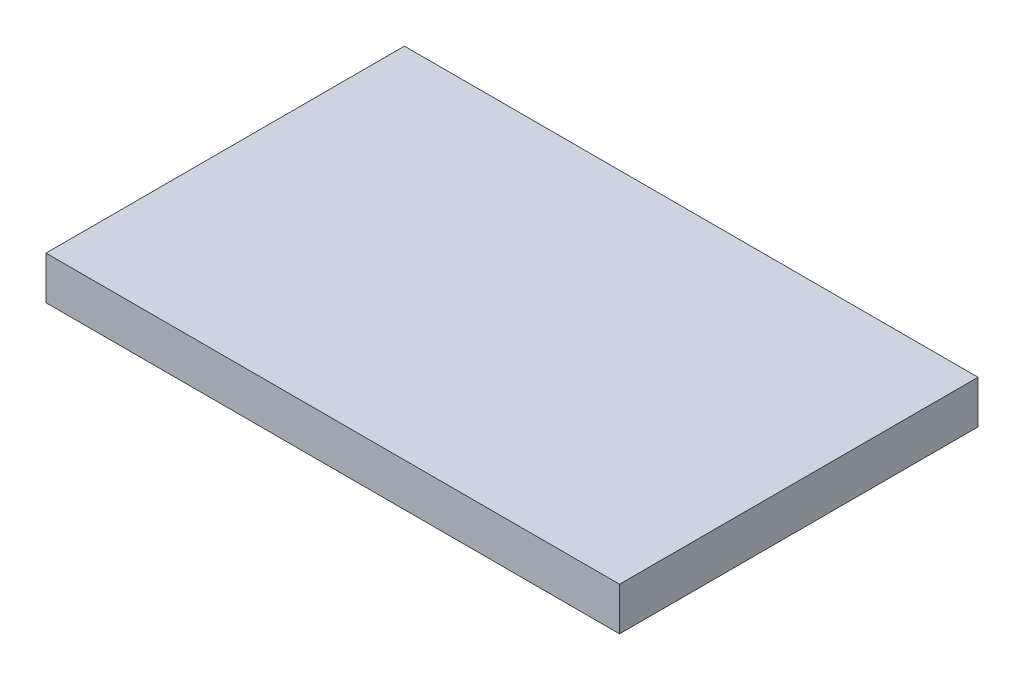
SolidWorks part; units mm, degrees
ref_plane "Front Plane" through (0, 0, 0) normal (0, 0, 1) x (1, 0, 0)
ref_plane "Top Plane" through (0, 0, 0) normal (0, 1, 0) x (1, 0, 0)
ref_plane "Right Plane" through (0, 0, 0) normal (1, 0, 0) x (0, 0, -1)
sketch "Sketch2" plane through (0, 0, 0) normal (0, 1, 0) x (1, 0, 0)
  line L1 (20, -12.5) -> (-20, -12.5)
  line L2 (20, -12.5) -> (20, 12.5)
  line L3 (20, 12.5) -> (-20, 12.5)
  line L4 (-20, -12.5) -> (-20, 12.5)
  line L5 (20, -12.5) -> (-20, 12.5) construction
  line L6 (20, 12.5) -> (-20, -12.5) construction
  point P0 (0, 0)
  dimension "D1" = 40
  dimension "D2" = 25
extrude "Boss-Extrude1" add sketch "Sketch2" against normal blind 3
sketch "Sketch3" [suppressed] plane through (0, 0, 0) normal (0, 1, 0) x (1, 0, 0)
  line L0 (20, 12.5) -> (-20, 12.5) construction
  line L1 (-19, 12.5) -> (-11.5, 12.5)
  line L2 (-19, 12.5) -> (-19, 2)
  line L3 (-19, 2) -> (-11.5, 2)
  line L4 (-11.5, 12.5) -> (-11.5, 2)
  line L5 (-20, 12.5) -> (-20, -12.5) construction
  dimension "D1" = 7.5
  dimension "D2" = 10.5
  dimension "D3" = 1
extrude "Boss-Extrude2" [suppressed] add sketch "Sketch3" along normal blind 10
sketch "Sketch4" [suppressed] plane through (0, 0, -2) normal (0, 0, 1) x (1, 0, 0)
  line L0 (-19, 7) -> (-18.1962, 10)
  line L1 (-19, 10) -> (-19, 0) construction
  line L2 (-19, 10) -> (-11.5, 10) construction
  line L3 (-18.1962, 10) -> (-19, 10)
  line L4 (-19, 10) -> (-19, 7)
  line L5 (-11.5, 7) -> (-13.2321, 10)
  line L6 (-11.5, 10) -> (-11.5, 0) construction
  line L7 (-13.2321, 10) -> (-11.5, 10)
  line L8 (-11.5, 10) -> (-11.5, 7)
  dimension "D1" = 3
  dimension "D2" = 3
  dimension "D3" = 15
  dimension "D4" = 30
extrude "Cut-Extrude1" [suppressed] cut sketch "Sketch4" against normal up to surface (10.5 mm away)
sketch "Sketch5" [suppressed] plane through (0, 10, 0) normal (0, 1, 0) x (1, 0, 0)
  line L0 (-13.2321, 12.5) -> (-18.1962, 12.5) construction
  line L1 (-17.4641, 7.522) -> (-13.9641, 7.522)
  line L2 (-17.4641, 7.522) -> (-17.4641, 7.222)
  line L3 (-17.4641, 7.222) -> (-13.9641, 7.222)
  line L4 (-13.9641, 7.522) -> (-13.9641, 7.222)
  line L5 (-19, 2) -> (-11.5, 2) construction
  circle A0 centre (-15.7141, 10) radius 1.75
  circle A1 centre (-15.7141, 4.5) radius 1.75
  point P10 (-15.7141, 12.5)
  point P11 (-15.7141, 7.522)
  dimension "D3" = 3.5
  dimension "D4" = 3.5
  dimension "D1" = 0.3
  dimension "D2" = 3.5
  dimension "D5" = 2.5
  dimension "D6" = 2.5
extrude "Cut-Extrude2" [suppressed] cut sketch "Sketch5" against normal blind 5
sketch "Sketch6" [suppressed] plane through (-19, 0, 0) normal (-1, 0, 0) x (0, 0, 1)
  line L0 (-2, 7) -> (-2, 0) construction
  line L1 (-12, 5.5) -> (-7.5, 5.5)
  line L2 (-12, 5.5) -> (-12, 1)
  line L3 (-12, 1) -> (-7.5, 1)
  line L4 (-7.5, 5.5) -> (-7.5, 1)
  line L5 (-12, 5.5) -> (-7.5, 1) construction
  line L6 (-12, 1) -> (-7.5, 5.5) construction
  line L7 (-7, 5.5) -> (-2.5, 5.5)
  line L8 (-7, 5.5) -> (-7, 1)
  line L9 (-7, 1) -> (-2.5, 1)
  line L10 (-2.5, 5.5) -> (-2.5, 1)
  line L11 (-7, 5.5) -> (-2.5, 1) construction
  line L12 (-7, 1) -> (-2.5, 5.5) construction
  line L13 (-12.5, 7) -> (-12.5, 0) construction
  line L14 (-12.5, 0) -> (-2, 0) construction
  point P0 (-9.75, 3.25)
  point P5 (-4.75, 3.25)
  dimension "D1" = 4.5
  dimension "D2" = 4.5
  dimension "D3" = 4.5
  dimension "D4" = 4.5
  dimension "D5" = 0.5
  dimension "D6" = 0.5
  dimension "D7" = 1
extrude "Cut-Extrude3" [suppressed] cut sketch "Sketch6" against normal blind 5
sketch "Sketch7" [suppressed] plane through (0, 0, 0) normal (0, 1, 0) x (1, 0, 0)
  line L0 (-20, 12.5) -> (-20, -12.5) construction
  line L1 (-11, -10) -> (-20, -10)
  line L2 (-11, -10) -> (-11, -2.5)
  line L3 (-11, -2.5) -> (-20, -2.5)
  line L4 (-20, -10) -> (-20, -2.5)
  line L5 (-11, -10) -> (-20, -2.5) construction
  line L6 (-11, -2.5) -> (-20, -10) construction
  line L7 (-20, -12.5) -> (20, -12.5) construction
  point P0 (-15.5, -6.25)
  dimension "D1" = 7.5
  dimension "D2" = 9
  dimension "D3" = 2.5
extrude "Boss-Extrude3" [suppressed] add sketch "Sketch7" along normal blind 3.5
sketch "Sketch8" [suppressed] plane through (-20, 0, 0) normal (-1, 0, 0) x (0, 0, 1)
  line L0 (6.25, 5.2143) -> (6.25, -0.441) construction
  line L1 (2.5, 3.5) -> (10, 3.5) construction
  line L2 (2.5, 3.5) -> (2.5, 0) construction
  line L3 (2.5, 0) -> (3.1127, 0)
  line L4 (2.5, 1.75) -> (2.5, 0)
  line L5 (10, 1.75) -> (10, 0)
  line L6 (10, 0) -> (9.3873, 0)
  spline S0 degree 3 poles (2.5, 1.75) (3.2855, 1.8357) (2.8866, -0.1418) (3.1127, 0) knots 0 0 0 0 1 1 1 1
  spline S1 degree 3 poles (10, 1.75) (9.2145, 1.8357) (9.6134, -0.1418) (9.3873, 0) knots 0 0 0 0 1 1 1 1
  point P4 (6.25, 3.5)
  line M15 (10, 0) -> (10, 3.5)
  line M17 (2.5, 3.5) -> (2.5, 0)
extrude "Cut-Extrude4" [suppressed] cut sketch "Sketch8" against normal blind 13.5 contours S0 L3 M17 | S1 L6 M15
fillet "Fillet1" [suppressed] radius 0.5
sketch "Sketch9" [suppressed] plane through (-20, 0, 0) normal (-1, 0, 0) x (0, 0, 1)
  line L0 (3.25, 0.25) -> (9.25, 0.25)
  line L1 (6.25, 3.8986) -> (6.25, 0.8013) construction
  line L2 (3, 3.5) -> (9.5, 3.5) construction
  line L3 (9.4263, 0) -> (12.5, 0) construction
  line L4 (9.4639, 3.25) -> (3.0361, 3.25)
  spline S0 degree 3 poles (9.25, 0.25) (9.2002, 0.8034) (9.2979, 1.1822) (9.4331, 1.8514) (9.7825, 1.9035) (9.8466, 2.3039) (9.7756, 2.7644) (9.8573, 3.2635) (9.4639, 3.25) knots 0 0 0 0 0.398944 0.460389 0.554943 0.650182 0.770421 1 1 1 1
  spline S1 degree 3 poles (3.25, 0.25) (3.2998, 0.8034) (3.2021, 1.1822) (3.0669, 1.8514) (2.7175, 1.9035) (2.6534, 2.3039) (2.7244, 2.7644) (2.6427, 3.2635) (3.0361, 3.25) knots 0 0 0 0 0.398944 0.460389 0.554943 0.650182 0.770421 1 1 1 1
  point P6 (6.25, 3.5)
  point P14 (6.25, 0.25)
  point P27 (6.25, 3.25)
  dimension "D1" = 3
  dimension "D2" = 0.25
  dimension "D3" = 0.25
extrude "Cut-Extrude5" [suppressed] cut sketch "Sketch9" against normal blind 8.5
sketch "Sketch10" [suppressed] plane through (0, 0, 0) normal (0, 1, 0) x (1, 0, 0)
  line L0 (-11.5, 2) -> (-11.5, 12.5) construction
  line L1 (-10, 9.5) -> (-7.5, 9.5)
  line L2 (-10, 9.5) -> (-10, 4.5)
  line L3 (-10, 4.5) -> (-7.5, 4.5)
  line L4 (-7.5, 9.5) -> (-7.5, 4.5)
  line L5 (-10, 9.5) -> (-7.5, 4.5) construction
  line L6 (-10, 4.5) -> (-7.5, 9.5) construction
  line L7 (20, 12.5) -> (-11.5, 12.5) construction
  point P0 (-8.75, 7)
  dimension "D1" = 5
  dimension "D2" = 2.5
  dimension "D3" = 1.5
  dimension "D4" = 3
extrude "Boss-Extrude4" [suppressed] add sketch "Sketch10" along normal blind 2
sketch "Sketch11" [suppressed] plane through (0, 2, 0) normal (0, 1, 0) x (1, 0, 0)
  line L0 (-7.5, 9.5) -> (-10, 9.5) construction
  line L1 (-8.5, 8) -> (-9, 8)
  line L2 (-8.5, 8) -> (-8.5, 8.5)
  line L3 (-8.5, 8.5) -> (-9, 8.5)
  line L4 (-9, 8) -> (-9, 8.5)
  line L5 (-8.5, 8) -> (-9, 8.5) construction
  line L6 (-8.5, 8.5) -> (-9, 8) construction
  line L7 (-8.5027, 5.5) -> (-9.0027, 5.5)
  line L8 (-8.5027, 5.5) -> (-8.5027, 6)
  line L9 (-8.5027, 6) -> (-9.0027, 6)
  line L10 (-9.0027, 5.5) -> (-9.0027, 6)
  line L11 (-8.5027, 5.5) -> (-9.0027, 6) construction
  line L12 (-8.5027, 6) -> (-9.0027, 5.5) construction
  line L13 (-7.5, 4.5) -> (-7.5, 9.5) construction
  line L14 (-10, 4.5) -> (-7.5, 4.5) construction
  point P0 (-8.75, 8.25)
  point P5 (-8.7527, 5.75)
  dimension "D1" = 0.5
  dimension "D2" = 0.5
  dimension "D3" = 0.5
  dimension "D4" = 0.5
  dimension "D5" = 1.25
  dimension "D6" = 1.25
  dimension "D7" = 1.2527
  dimension "D8" = 1.25
extrude "Boss-Extrude5" [suppressed] add sketch "Sketch11" along normal blind 5
sketch "Sketch12" [suppressed] plane through (0, 0, 0) normal (0, 1, 0) x (1, 0, 0)
  line L0 (-11, -9.5) -> (-11, -3) construction
  line L1 (-8.5, -9.75) -> (1.5, -9.75)
  line L2 (-8.5, -9.75) -> (-8.5, -12.25)
  line L3 (-8.5, -12.25) -> (1.5, -12.25)
  line L4 (1.5, -9.75) -> (1.5, -12.25)
  line L5 (-20, -12.5) -> (20, -12.5) construction
  dimension "D1" = 2.5
  dimension "D2" = 10
  dimension "D3" = 2.5
  dimension "D4" = 0.25
extrude "Boss-Extrude6" [suppressed] add sketch "Sketch12" along normal blind 2
sketch "Sketch13" [suppressed] plane through (0, 2, 0) normal (0, 1, 0) x (1, 0, 0)
  line L0 (-8.5, -9.75) -> (-8.5, -12.25) construction
  line L1 (-7, -11.25) -> (-7.5, -11.25)
  line L2 (-7, -11.25) -> (-7, -10.75)
  line L3 (-7, -10.75) -> (-7.5, -10.75)
  line L4 (-7.5, -11.25) -> (-7.5, -10.75)
  line L5 (-7, -11.25) -> (-7.5, -10.75) construction
  line L6 (-7, -10.75) -> (-7.5, -11.25) construction
  line L8 (1.5, -9.75) -> (-8.5, -9.75) construction
  line L9 (-5, -11.25) -> (-5, -10.75)
  line L10 (-4.5, -10.75) -> (-5, -10.75)
  line L11 (-4.5, -11.25) -> (-4.5, -10.75)
  line L12 (-4.5, -11.25) -> (-5, -11.25)
  line L13 (-2.5, -11.25) -> (-2.5, -10.75)
  line L14 (-2, -10.75) -> (-2.5, -10.75)
  line L15 (-2, -11.25) -> (-2, -10.75)
  line L16 (-2, -11.25) -> (-2.5, -11.25)
  line L17 (0, -11.25) -> (0, -10.75)
  line L18 (0.5, -10.75) -> (0, -10.75)
  line L19 (0.5, -11.25) -> (0.5, -10.75)
  line L20 (0.5, -11.25) -> (0, -11.25)
  point P0 (-7.25, -11)
  dimension "D1" = 1.25
  dimension "D2" = 1.25
  dimension "D3" = 0.5
  dimension "D4" = 0.5
  dimension "D5" = 4
extrude "Boss-Extrude7" [suppressed] add sketch "Sketch13" along normal blind 5
sketch "Sketch14" [suppressed] plane through (0, 0, 0) normal (0, 1, 0) x (1, 0, 0)
  line L0 (-7.5, 4.5) -> (-7.5, 9.5) construction
  line L1 (-6.5, 5.5) -> (1.5, 5.5)
  line L2 (-6.5, 5.5) -> (-6.5, 1.5)
  line L3 (-6.5, 1.5) -> (1.5, 1.5)
  line L4 (1.5, 5.5) -> (1.5, 1.5)
  line L5 (-8.5, -3.5) -> (1.5, -3.5)
  line L6 (-8.5, -3.5) -> (-8.5, -7.5)
  line L7 (-8.5, -7.5) -> (1.5, -7.5)
  line L8 (1.5, -3.5) -> (1.5, -7.5)
  line L9 (20, 12.5) -> (-11.5, 12.5) construction
  dimension "D1" = 8
  dimension "D2" = 4
  dimension "D3" = 4
  dimension "D4" = 10
  dimension "D5" = 1
  dimension "D6" = 7
  dimension "D7" = 5
extrude "Boss-Extrude8" [suppressed] add sketch "Sketch14" along normal blind 1
sketch "Sketch15" [suppressed] plane through (1.5, 0, 0) normal (1, 0, 0) x (0, 0, -1)
  line L0 (1.5, 0.7025) -> (1.3027, 0.7025)
  line L1 (1.5, 1) -> (1.5, 0) construction
  line L2 (1.0838, 0.6521) -> (0.9577, 0.5907)
  line L3 (0.704, 0.3042) -> (0.599, 0)
  line L4 (-12.5, 0) -> (12.5, 0) construction
  line L5 (0.599, 0) -> (0.8295, 0)
  line L6 (0.8295, 0) -> (0.9119, 0.2391)
  line L7 (1.1657, 0.5256) -> (1.216, 0.5501)
  line L8 (1.216, 0.5501) -> (1.5, 0.5501)
  line L9 (3.5, 2.4985) -> (3.5, 0.0788) construction
  line L10 (1.5, 1) -> (5.5, 1) construction
  line L11 (1.5, 0.7025) -> (1.5, 0.5501)
  line L12 (5.5, 0.7025) -> (5.5, 0.5501)
  line L13 (5.784, 0.5501) -> (5.5, 0.5501)
  line L14 (5.8343, 0.5256) -> (5.784, 0.5501)
  line L15 (6.1705, 0) -> (6.0881, 0.2391)
  line L16 (6.401, 0) -> (6.1705, 0)
  line L17 (6.296, 0.3042) -> (6.401, 0)
  line L18 (5.9162, 0.6521) -> (6.0423, 0.5907)
  line L19 (5.5, 0.7025) -> (5.6973, 0.7025)
  arc A0 (1.3027, 0.7025) -> (1.0838, 0.6521) centre (1.3027, 0.2025) ccw
  arc A1 (0.9119, 0.2391) -> (1.1657, 0.5256) centre (1.3846, 0.076) cw
  arc A2 (0.704, 0.3042) -> (0.9577, 0.5907) centre (1.1767, 0.1412) cw
  arc A3 (6.296, 0.3042) -> (6.0423, 0.5907) centre (5.8233, 0.1412) ccw
  arc A4 (6.0881, 0.2391) -> (5.8343, 0.5256) centre (5.6154, 0.076) ccw
  arc A5 (5.6973, 0.7025) -> (5.9162, 0.6521) centre (5.6973, 0.2025) cw
  point P16 (3.5, 1)
  dimension "D1" = 0.5
extrude "Boss-Extrude9" [suppressed] add sketch "Sketch15" against normal up to surface (8 mm away)
sketch "Sketch16" [suppressed] plane through (1.5, 0, 0) normal (1, 0, 0) x (0, 0, -1)
  line L0 (-7.5, 0.6782) -> (-7.7045, 0.6782)
  line L1 (-7.5, 1) -> (-7.5, 0) construction
  line L2 (-7.8691, 0.6503) -> (-7.9154, 0.6342)
  line L3 (-8.1339, 0.4833) -> (-8.2332, 0.3648)
  line L4 (-8.3282, 0.1901) -> (-8.3864, 0)
  line L5 (-12.5, 0) -> (12.5, 0) construction
  line L6 (-8.3864, 0) -> (-8.2252, 0)
  line L7 (-8.2252, 0) -> (-8.1768, 0.1579)
  line L8 (-8.0819, 0.3327) -> (-8.0568, 0.3626)
  line L9 (-7.9199, 0.4766) -> (-7.8668, 0.5066)
  line L10 (-7.6206, 0.5714) -> (-7.5, 0.5714)
  line L11 (-7.5, 0.6782) -> (-7.5, 0.5714)
  line L12 (-5.5, 2.2485) -> (-5.5, -1.2373) construction
  line L13 (-7.5, 1) -> (-3.5, 1) construction
  line L14 (-3.5, 0.6782) -> (-3.5, 0.5714)
  line L15 (-3.3794, 0.5714) -> (-3.5, 0.5714)
  line L16 (-3.0801, 0.4766) -> (-3.1332, 0.5066)
  line L17 (-2.9181, 0.3327) -> (-2.9432, 0.3626)
  line L18 (-2.7748, 0) -> (-2.8232, 0.1579)
  line L19 (-2.6136, 0) -> (-2.7748, 0)
  line L20 (-2.6718, 0.1901) -> (-2.6136, 0)
  line L21 (-2.8661, 0.4833) -> (-2.7668, 0.3648)
  line L22 (-3.1309, 0.6503) -> (-3.0846, 0.6342)
  line L23 (-3.5, 0.6782) -> (-3.2955, 0.6782)
  arc A1 (-7.7045, 0.6782) -> (-7.8691, 0.6503) centre (-7.7045, 0.1782) ccw
  arc A2 (-7.8668, 0.5066) -> (-7.6206, 0.5714) centre (-7.6206, 0.0714) cw
  arc A3 (-8.0568, 0.3626) -> (-7.9199, 0.4766) centre (-7.6737, 0.0414) cw
  arc A4 (-8.1768, 0.1579) -> (-8.0819, 0.3327) centre (-7.6987, 0.0115) cw
  arc A5 (-8.2332, 0.3648) -> (-8.3282, 0.1901) centre (-7.8501, 0.0436) ccw
  arc A6 (-7.9154, 0.6342) -> (-8.1339, 0.4833) centre (-7.7508, 0.1621) ccw
  arc A7 (-3.0846, 0.6342) -> (-2.8661, 0.4833) centre (-3.2492, 0.1621) cw
  arc A8 (-2.7668, 0.3648) -> (-2.6718, 0.1901) centre (-3.1499, 0.0436) cw
  arc A9 (-2.8232, 0.1579) -> (-2.9181, 0.3327) centre (-3.3013, 0.0115) ccw
  arc A10 (-2.9432, 0.3626) -> (-3.0801, 0.4766) centre (-3.3263, 0.0414) ccw
  arc A11 (-3.1332, 0.5066) -> (-3.3794, 0.5714) centre (-3.3794, 0.0714) ccw
  arc A12 (-3.2955, 0.6782) -> (-3.1309, 0.6503) centre (-3.2955, 0.1782) cw
  point P16 (-5.5, 1)
  dimension "D1" = 0.5
extrude "Boss-Extrude10" [suppressed] add sketch "Sketch16" against normal up to surface (10 mm away)
sketch "Sketch17" [suppressed] plane through (0, 0, 0) normal (0, 1, 0) x (1, 0, 0)
  line L0 (-6.5, 6.401) -> (1.5, 6.401) construction
  line L1 (-5.9, 6.401) -> (-5.3, 6.401)
  line L2 (-5.9, 6.401) -> (-5.9, 5.5)
  line L3 (-5.9, 5.5) -> (-5.3, 5.5)
  line L4 (-5.3, 6.401) -> (-5.3, 5.5)
  line L5 (-6.5, 5.5) -> (1.5, 5.5) construction
  line L6 (-6.5, 1.5) -> (1.5, 1.5) construction
  line L7 (-5.9, 1.5) -> (-5.3, 1.5)
  line L8 (-5.9, 1.5) -> (-5.9, 0.599)
  line L9 (-5.9, 0.599) -> (-5.3, 0.599)
  line L10 (-5.3, 1.5) -> (-5.3, 0.599)
  line L11 (-6.5, 0.599) -> (1.5, 0.599) construction
  line L12 (-6.5, 6.296) -> (-6.5, 6.0423) construction
  line L13 (-4.1, 1.5) -> (-4.1, 0.599)
  line L14 (-4.7, 1.5) -> (-4.1, 1.5)
  line L15 (-4.7, 1.5) -> (-4.7, 0.599)
  line L16 (-4.7, 0.599) -> (-4.1, 0.599)
  line L17 (-4.7, 5.5) -> (-4.1, 5.5)
  line L18 (-4.7, 6.401) -> (-4.7, 5.5)
  line L19 (-4.1, 6.401) -> (-4.1, 5.5)
  line L20 (-4.7, 6.401) -> (-4.1, 6.401)
  line L21 (-2.9, 1.5) -> (-2.9, 0.599)
  line L22 (-3.5, 1.5) -> (-2.9, 1.5)
  line L23 (-3.5, 1.5) -> (-3.5, 0.599)
  line L24 (-3.5, 0.599) -> (-2.9, 0.599)
  line L25 (-3.5, 5.5) -> (-2.9, 5.5)
  line L26 (-3.5, 6.401) -> (-3.5, 5.5)
  line L27 (-2.9, 6.401) -> (-2.9, 5.5)
  line L28 (-3.5, 6.401) -> (-2.9, 6.401)
  line L29 (-1.7, 1.5) -> (-1.7, 0.599)
  line L30 (-2.3, 1.5) -> (-1.7, 1.5)
  line L31 (-2.3, 1.5) -> (-2.3, 0.599)
  line L32 (-2.3, 0.599) -> (-1.7, 0.599)
  line L33 (-2.3, 5.5) -> (-1.7, 5.5)
  line L34 (-2.3, 6.401) -> (-2.3, 5.5)
  line L35 (-1.7, 6.401) -> (-1.7, 5.5)
  line L36 (-2.3, 6.401) -> (-1.7, 6.401)
  line L37 (-0.5, 1.5) -> (-0.5, 0.599)
  line L38 (-1.1, 1.5) -> (-0.5, 1.5)
  line L39 (-1.1, 1.5) -> (-1.1, 0.599)
  line L40 (-1.1, 0.599) -> (-0.5, 0.599)
  line L41 (-1.1, 5.5) -> (-0.5, 5.5)
  line L42 (-1.1, 6.401) -> (-1.1, 5.5)
  line L43 (-0.5, 6.401) -> (-0.5, 5.5)
  line L44 (-1.1, 6.401) -> (-0.5, 6.401)
  line L45 (0.7, 1.5) -> (0.7, 0.599)
  line L46 (0.1, 1.5) -> (0.7, 1.5)
  line L47 (0.1, 1.5) -> (0.1, 0.599)
  line L48 (0.1, 0.599) -> (0.7, 0.599)
  line L49 (0.1, 5.5) -> (0.7, 5.5)
  line L50 (0.1, 6.401) -> (0.1, 5.5)
  line L51 (0.7, 6.401) -> (0.7, 5.5)
  line L52 (0.1, 6.401) -> (0.7, 6.401)
  line L53 (-8.5, -2.6136) -> (1.5, -2.6136) construction
  line L54 (-7.9, -2.6136) -> (-7.3, -2.6136)
  line L55 (-7.9, -2.6136) -> (-7.9, -3.5)
  line L56 (-7.9, -3.5) -> (-7.3, -3.5)
  line L57 (-7.3, -2.6136) -> (-7.3, -3.5)
  line L58 (1.5, -3.5) -> (-8.5, -3.5) construction
  line L59 (-8.5, -7.5) -> (1.5, -7.5) construction
  line L60 (-7.9, -7.5) -> (-7.3, -7.5)
  line L61 (-7.9, -7.5) -> (-7.9, -8.3864)
  line L62 (-7.9, -8.3864) -> (-7.3, -8.3864)
  line L63 (-7.3, -7.5) -> (-7.3, -8.3864)
  line L64 (-8.5, -8.3864) -> (1.5, -8.3864) construction
  line L65 (-8.5, -2.8661) -> (-8.5, -3.0846) construction
  line L66 (-8.5, -7.7045) -> (-8.5, -7.8691) construction
  line L67 (-6.7, -2.6136) -> (-6.7, -3.5)
  line L68 (-6.7, -2.6136) -> (-6.1, -2.6136)
  line L69 (-6.1, -2.6136) -> (-6.1, -3.5)
  line L70 (-6.7, -3.5) -> (-6.1, -3.5)
  line L71 (-6.7, -7.5) -> (-6.7, -8.3864)
  line L72 (-6.7, -7.5) -> (-6.1, -7.5)
  line L73 (-6.1, -7.5) -> (-6.1, -8.3864)
  line L74 (-6.7, -8.3864) -> (-6.1, -8.3864)
  line L75 (-5.5, -2.6136) -> (-5.5, -3.5)
  line L76 (-5.5, -2.6136) -> (-4.9, -2.6136)
  line L77 (-4.9, -2.6136) -> (-4.9, -3.5)
  line L78 (-5.5, -3.5) -> (-4.9, -3.5)
  line L79 (-5.5, -7.5) -> (-5.5, -8.3864)
  line L80 (-5.5, -7.5) -> (-4.9, -7.5)
  line L81 (-4.9, -7.5) -> (-4.9, -8.3864)
  line L82 (-5.5, -8.3864) -> (-4.9, -8.3864)
  line L83 (-4.3, -2.6136) -> (-4.3, -3.5)
  line L84 (-4.3, -2.6136) -> (-3.7, -2.6136)
  line L85 (-3.7, -2.6136) -> (-3.7, -3.5)
  line L86 (-4.3, -3.5) -> (-3.7, -3.5)
  line L87 (-4.3, -7.5) -> (-4.3, -8.3864)
  line L88 (-4.3, -7.5) -> (-3.7, -7.5)
  line L89 (-3.7, -7.5) -> (-3.7, -8.3864)
  line L90 (-4.3, -8.3864) -> (-3.7, -8.3864)
  line L91 (-3.1, -2.6136) -> (-3.1, -3.5)
  line L92 (-3.1, -2.6136) -> (-2.5, -2.6136)
  line L93 (-2.5, -2.6136) -> (-2.5, -3.5)
  line L94 (-3.1, -3.5) -> (-2.5, -3.5)
  line L95 (-3.1, -7.5) -> (-3.1, -8.3864)
  line L96 (-3.1, -7.5) -> (-2.5, -7.5)
  line L97 (-2.5, -7.5) -> (-2.5, -8.3864)
  line L98 (-3.1, -8.3864) -> (-2.5, -8.3864)
  line L99 (-1.9, -2.6136) -> (-1.9, -3.5)
  line L100 (-1.9, -2.6136) -> (-1.3, -2.6136)
  line L101 (-1.3, -2.6136) -> (-1.3, -3.5)
  line L102 (-1.9, -3.5) -> (-1.3, -3.5)
  line L103 (-1.9, -7.5) -> (-1.9, -8.3864)
  line L104 (-1.9, -7.5) -> (-1.3, -7.5)
  line L105 (-1.3, -7.5) -> (-1.3, -8.3864)
  line L106 (-1.9, -8.3864) -> (-1.3, -8.3864)
  line L107 (-0.7, -2.6136) -> (-0.7, -3.5)
  line L108 (-0.7, -2.6136) -> (-0.1, -2.6136)
  line L109 (-0.1, -2.6136) -> (-0.1, -3.5)
  line L110 (-0.7, -3.5) -> (-0.1, -3.5)
  line L111 (-0.7, -7.5) -> (-0.7, -8.3864)
  line L112 (-0.7, -7.5) -> (-0.1, -7.5)
  line L113 (-0.1, -7.5) -> (-0.1, -8.3864)
  line L114 (-0.7, -8.3864) -> (-0.1, -8.3864)
  line L115 (0.5, -2.6136) -> (0.5, -3.5)
  line L116 (0.5, -2.6136) -> (1.1, -2.6136)
  line L117 (1.1, -2.6136) -> (1.1, -3.5)
  line L118 (0.5, -3.5) -> (1.1, -3.5)
  line L119 (0.5, -7.5) -> (0.5, -8.3864)
  line L120 (0.5, -7.5) -> (1.1, -7.5)
  line L121 (1.1, -7.5) -> (1.1, -8.3864)
  line L122 (0.5, -8.3864) -> (1.1, -8.3864)
  dimension "D1" = 0.6
  dimension "D2" = 0.6
  dimension "D3" = 0.6
  dimension "D5" = 0.6
  dimension "D6" = 0.6
  dimension "D7" = 0.6
  dimension "D8" = 0.6
  dimension "D4" = 6
  dimension "D9" = 8
extrude "Cut-Extrude6" [suppressed] cut sketch "Sketch17" along normal blind 1
sketch "Sketch18" [suppressed] plane through (0, 0, 0) normal (0, 1, 0) x (1, 0, 0)
  line L0 (15.25, 10) -> (19.75, 10)
  line L1 (19.75, 10) -> (19.75, 0.5)
  line L2 (19.75, 0.5) -> (16.75, 0.5)
  line L5 (16.75, 0.5) -> (15.25, 2)
  line L6 (15.25, 2) -> (15.25, 10)
  line L7 (20, -12.5) -> (20, 12.5) construction
  line L8 (20, 12.5) -> (-11.5, 12.5) construction
  line L9 (15.25, -0.75) -> (19.75, -0.75)
  line L10 (19.75, -0.75) -> (19.75, -10.25)
  line L11 (19.75, -10.25) -> (16.75, -10.25)
  line L12 (16.75, -10.25) -> (15.25, -8.75)
  line L13 (15.25, -8.75) -> (15.25, -0.75)
  line L14 (-20, -12.5) -> (20, -12.5) construction
  line L21 (11, 7.5) -> (14.5, 7.5)
  line L22 (11, 7.5) -> (11, 1)
  line L23 (11, 1) -> (14.5, 1)
  line L24 (14.5, 7.5) -> (14.5, 1)
  line L25 (11, 0.25) -> (14.5, 0.25)
  line L26 (11, 0.25) -> (11, -6.25)
  line L27 (11, -6.25) -> (14.5, -6.25)
  line L28 (14.5, 0.25) -> (14.5, -6.25)
  dimension "D1" = 9.5
  dimension "D2" = 4.5
  dimension "D3" = 135
  dimension "D4" = 0.25
  dimension "D5" = 2.5
  dimension "D6" = 3
  dimension "D7" = 135
  dimension "D8" = 3
  dimension "D9" = 9.5
  dimension "D10" = 4.5
  dimension "D11" = 0.25
  dimension "D12" = 2.25
  dimension "D13" = 3.5
  dimension "D14" = 3.5
  dimension "D15" = 6.5
  dimension "D16" = 6.5
  dimension "D17" = 0.75
  dimension "D18" = 0.75
  dimension "D19" = 2.5
  dimension "D20" = 0.75
extrude "Extrude-Thin1" [suppressed] add sketch "Sketch18" along normal blind 5.5 thin
sketch "Sketch19" [suppressed] plane through (0, 0, 0) normal (0, 1, 0) x (1, 0, 0)
  line L0 (19.75, 0.5) -> (19.75, 10) construction
  line L1 (11, 7.5) -> (14.5, 7.5)
  line L2 (11, 7.5) -> (11, 1)
  line L3 (11, 1) -> (14.5, 1)
  line L4 (14.5, 7.5) -> (14.5, 1)
  line L5 (11, 0.25) -> (14.5, 0.25)
  line L6 (11, 0.25) -> (11, -6.25)
  line L7 (11, -6.25) -> (14.5, -6.25)
  line L8 (14.5, 0.25) -> (14.5, -6.25)
  line L9 (19.75, 10) -> (15.25, 10) construction
  line L10 (15.25, 10) -> (15.25, 2) construction
  line L11 (15.25, 2) -> (16.75, 0.5) construction
  line L12 (16.75, 0.5) -> (19.75, 0.5) construction
  line L13 (19.75, -10.25) -> (19.75, -0.75) construction
  line L14 (19.75, -0.75) -> (15.25, -0.75) construction
  line L15 (15.25, -0.75) -> (15.25, -8.75) construction
  line L16 (15.25, -8.75) -> (16.75, -10.25) construction
  line L17 (16.75, -10.25) -> (19.75, -10.25) construction
  line L18 (19.75, 0.5) -> (19.75, 10)
  line L19 (19.75, 10) -> (15.25, 10)
  line L20 (15.25, 10) -> (15.25, 2)
  line L21 (15.25, 2) -> (16.75, 0.5)
  line L22 (16.75, 0.5) -> (19.75, 0.5)
  line L23 (19.75, -10.25) -> (19.75, -0.75)
  line L24 (19.75, -0.75) -> (15.25, -0.75)
  line L25 (15.25, -0.75) -> (15.25, -8.75)
  line L26 (15.25, -8.75) -> (16.75, -10.25)
  line L27 (16.75, -10.25) -> (19.75, -10.25)
extrude "Boss-Extrude11" [suppressed] add sketch "Sketch19" along normal blind 1.5
sketch "Sketch20" [suppressed] plane through (0, 1.5, 0) normal (0, 1, 0) x (1, 0, 0)
  line L0 (16.5, 5.25) -> (17, 5.25)
  line L1 (16.5, 8) -> (17, 8)
  line L2 (16.5, 8) -> (16.5, 7.5)
  line L3 (16.5, 7.5) -> (17, 7.5)
  line L4 (17, 8) -> (17, 7.5)
  line L5 (16.5, 5.25) -> (16.5, 5.75)
  line L6 (16.5, 5.75) -> (17, 5.75)
  line L7 (17, 5.25) -> (17, 5.75)
  line L8 (16.5, 3.5) -> (17, 3.5)
  line L9 (16.5, 3.5) -> (16.5, 3)
  line L10 (16.5, 3) -> (17, 3)
  line L11 (17, 3.5) -> (17, 3)
  line L12 (16.5, -2.75) -> (17, -2.75)
  line L13 (16.5, -2.75) -> (16.5, -3.25)
  line L14 (16.5, -3.25) -> (17, -3.25)
  line L15 (17, -2.75) -> (17, -3.25)
  line L16 (16.5, -5) -> (17, -5)
  line L17 (16.5, -5) -> (16.5, -5.5)
  line L18 (16.5, -5.5) -> (17, -5.5)
  line L19 (17, -5) -> (17, -5.5)
  line L20 (16.5, -7.25) -> (17, -7.25)
  line L21 (16.5, -7.25) -> (16.5, -7.75)
  line L22 (16.5, -7.75) -> (17, -7.75)
  line L23 (17, -7.25) -> (17, -7.75)
  line L24 (12.5, -0.5) -> (13, -0.5)
  line L25 (12.5, -0.5) -> (12.5, -1)
  line L26 (12.5, -1) -> (13, -1)
  line L27 (13, -0.5) -> (13, -1)
  line L28 (12.5, -2.5) -> (13, -2.5)
  line L29 (12.5, -2.5) -> (12.5, -3)
  line L30 (12.5, -3) -> (13, -3)
  line L31 (13, -2.5) -> (13, -3)
  line L32 (12.5, -4.5) -> (13, -4.5)
  line L33 (12.5, -4.5) -> (12.5, -5)
  line L34 (12.5, -5) -> (13, -5)
  line L35 (13, -4.5) -> (13, -5)
  line L36 (12.5, 2.75) -> (13, 2.75)
  line L37 (12.5, 2.75) -> (12.5, 2.25)
  line L38 (12.5, 2.25) -> (13, 2.25)
  line L39 (13, 2.75) -> (13, 2.25)
  line L40 (12.5, 4.75) -> (13, 4.75)
  line L41 (12.5, 4.75) -> (12.5, 4.25)
  line L42 (12.5, 4.25) -> (13, 4.25)
  line L43 (13, 4.75) -> (13, 4.25)
  line L44 (12.5, 5.75) -> (13, 5.75)
  line L45 (12.5, 5.75) -> (12.5, 6.25)
  line L46 (12.5, 6.25) -> (13, 6.25)
  line L47 (13, 5.75) -> (13, 6.25)
  line L48 (11, 1) -> (14.5, 1) construction
  line L49 (11, 7.5) -> (11, 1) construction
  line L51 (11, -6.25) -> (14.5, -6.25) construction
  line L52 (19.75, 10) -> (15.25, 10) construction
  line L53 (15.25, 10) -> (15.25, 2) construction
  line L55 (19.75, -0.75) -> (15.25, -0.75) construction
  dimension "D1" = 0.5
  dimension "D2" = 0.5
  dimension "D3" = 1.5
  dimension "D4" = 1.5
  dimension "D5" = 1.25
  dimension "D6" = 1.5
  dimension "D7" = 0.5
  dimension "D8" = 0.5
  dimension "D9" = 0.5
  dimension "D10" = 0.5
  dimension "D11" = 0.5
  dimension "D12" = 0.5
  dimension "D13" = 0.5
  dimension "D14" = 0.5
  dimension "D15" = 0.5
  dimension "D16" = 0.5
  dimension "D17" = 1.25
  dimension "D18" = 1.5
  dimension "D19" = 1.5
  dimension "D20" = 0.5
  dimension "D21" = 0.5
  dimension "D22" = 1.75
  dimension "D23" = 1.75
  dimension "D24" = 2
  dimension "D25" = 1.25
  dimension "D26" = 1.75
  dimension "D27" = 1.75
  dimension "D28" = 0.5
  dimension "D29" = 0.5
  dimension "D30" = 0.5
  dimension "D31" = 0.5
  dimension "D32" = 2
extrude "Boss-Extrude12" [suppressed] add sketch "Sketch20" along normal up to surface (4 mm away)
ref_plane "Plane1" [suppressed] through (6.5, 0, 0) normal (1, 0, 0) x (0, 0, -1)
sketch "Sketch21" [suppressed] plane through (6.5, 0, 0) normal (1, 0, 0) x (0, 0, -1)
  line L0 (-8.8936, 0.7228) -> (16.1457, 7.4321) construction
  line L1 (-2.6456, 0) -> (5.105, 0) construction
  line L2 (-5.5, 1.6321) -> (-5.1118, 0.1832)
  line L3 (-3.6099, 0.5856) -> (6.4793, 3.289)
  line L4 (6.4793, 3.289) -> (6.0911, 4.7379)
  line L5 (-5.1118, 0.1832) -> (-4.6288, 0.3126)
  line L6 (-5.5, 1.6321) -> (6.0911, 4.7379)
  arc A0 (-3.6099, 0.5856) -> (-4.6288, 0.3126) centre (-4.1597, 0.5998) ccw
  dimension "D3" = 0.55
  dimension "D1" = 15
  dimension "D2" = 3
  dimension "D4" = 1.5
  dimension "D5" = 12
  dimension "D6" = 0.5
  dimension "D7" = 5.5
revolve "Revolve1" [suppressed] add sketch "Sketch21" angle 360 about L0
sketch "Sketch22" [suppressed] plane through (6.5, 0, 0) normal (1, 0, 0) x (0, 0, -1)
  line L0 (-0.2315, 0) -> (-9.1302, 0) construction
  line L1 (-5.3855, 1.2048) -> (-5.9749, 0.9066)
  line L2 (-5.8882, 3.081) -> (-5.1118, 0.1832) construction
  line L3 (-6.3822, 0.5266) -> (-6.4098, 0.4803)
  line L4 (-6.4684, 0.3662) -> (-6.6273, 0)
  line L5 (-6.6273, 0) -> (-6.8363, 0)
  line L6 (-6.8363, 0) -> (-6.7304, 0.3506)
  line L7 (-6.632, 0.5737) -> (-6.6309, 0.5755)
  line L8 (-6.3158, 0.9024) -> (-5.4541, 1.4608)
  line L9 (-5.4541, 1.4608) -> (-5.3855, 1.2048)
  arc A0 (-5.9749, 0.9066) -> (-6.3822, 0.5266) centre (-5.5234, 0.0143) ccw
  arc A1 (-6.4098, 0.4803) -> (-6.4684, 0.3662) centre (-5.551, -0.0319) ccw
  arc A2 (-6.7304, 0.3506) -> (-6.632, 0.5737) centre (-5.7732, 0.0614) cw
  arc A3 (-6.6309, 0.5755) -> (-6.3158, 0.9024) centre (-5.7721, 0.0632) cw
  dimension "D1" = 1
extrude "Boss-Extrude13" [suppressed] add sketch "Sketch22" along normal mid plane 1.5
sketch "Sketch24" [suppressed] plane through (0, 0, 12.5) normal (0, 0, 1) x (1, 0, 0)
  line L0 (7.25, 1.4608) -> (5.75, 1.4608) construction
  line L1 (6.05, 1.4608) -> (6.95, 1.4608)
  line L2 (6.05, 1.4608) -> (6.05, 0)
  line L3 (6.05, 0) -> (6.95, 0)
  line L4 (6.95, 1.4608) -> (6.95, 0)
  line L5 (-20, 0) -> (20, 0) construction
  line L6 (5.75, 1.4608) -> (5.75, 0.9024) construction
  line L7 (7.25, 1.4608) -> (7.25, 0.9024) construction
  dimension "D1" = 0.3
  dimension "D2" = 0.3
extrude "Cut-Extrude7" [suppressed] cut sketch "Sketch24" against normal blind 7
sketch "Sketch25" [suppressed] plane through (0, 0, 0) normal (0, 1, 0) x (1, 0, 0)
  line L0 (3.6854, 8.6309) -> (2.1854, 8.6309)
  line L1 (-3.6277, 8.6309) -> (-5.1277, 8.6309)
  line L2 (-3.6277, 8.6309) -> (-3.6277, 11.1309)
  line L3 (-3.6277, 11.1309) -> (-5.1277, 11.1309)
  line L4 (-5.1277, 8.6309) -> (-5.1277, 11.1309)
  line L5 (-3.6277, 8.6309) -> (-5.1277, 11.1309) construction
  line L6 (-3.6277, 11.1309) -> (-5.1277, 8.6309) construction
  line L7 (3.6854, 8.6309) -> (3.6854, 11.1309)
  line L8 (3.6854, 11.1309) -> (2.1854, 11.1309)
  line L9 (2.1854, 8.6309) -> (2.1854, 11.1309)
  line L10 (3.6854, 8.6309) -> (2.1854, 11.1309) construction
  line L11 (3.6854, 11.1309) -> (2.1854, 8.6309) construction
  line L12 (6.8331, 8.6309) -> (5.3331, 8.6309)
  line L13 (6.8331, 8.6309) -> (6.8331, 11.1309)
  line L14 (6.8331, 11.1309) -> (5.3331, 11.1309)
  line L15 (5.3331, 8.6309) -> (5.3331, 11.1309)
  line L16 (6.8331, 8.6309) -> (5.3331, 11.1309) construction
  line L17 (6.8331, 11.1309) -> (5.3331, 8.6309) construction
  line L18 (9.6668, 8.6309) -> (8.1668, 8.6309)
  line L19 (9.6668, 8.6309) -> (9.6668, 11.1309)
  line L20 (9.6668, 11.1309) -> (8.1668, 11.1309)
  line L21 (8.1668, 8.6309) -> (8.1668, 11.1309)
  line L22 (9.6668, 8.6309) -> (8.1668, 11.1309) construction
  line L23 (9.6668, 11.1309) -> (8.1668, 8.6309) construction
  line L24 (4.0958, -5.2967) -> (2.6919, -5.2967)
  line L25 (4.0958, -5.2967) -> (4.0958, -2.7967)
  line L26 (4.0958, -2.7967) -> (2.6919, -2.7967)
  line L27 (2.6919, -5.2967) -> (2.6919, -2.7967)
  line L28 (4.0958, -5.2967) -> (2.6919, -2.7967) construction
  line L29 (4.0958, -2.7967) -> (2.6919, -5.2967) construction
  line L30 (4.0958, -9.3613) -> (2.6919, -9.3613)
  line L31 (4.0958, -9.3613) -> (4.0958, -6.8613)
  line L32 (4.0958, -6.8613) -> (2.6919, -6.8613)
  line L33 (2.6919, -9.3613) -> (2.6919, -6.8613)
  line L34 (4.0958, -9.3613) -> (2.6919, -6.8613) construction
  line L35 (4.0958, -6.8613) -> (2.6919, -9.3613) construction
  point P0 (-4.3777, 9.8809)
  point P6 (2.9354, 9.8809)
  point P11 (6.0831, 9.8809)
  point P16 (8.9168, 9.8809)
  point P23 (3.3938, -4.0467)
  point P28 (3.3938, -8.1113)
  dimension "D1" = 1.5
  dimension "D2" = 2.5
  dimension "D3" = 2.5
  dimension "D4" = 2.5
  dimension "D5" = 2.5
  dimension "D6" = 2.5
  dimension "D7" = 2.5
extrude "Boss-Extrude14" [suppressed] add sketch "Sketch25" along normal blind 1
ref_plane "Plane2" [suppressed] through (0, -3, 0) normal (0, 1, 0) x (1, 0, 0)
sketch "Sketch26" [suppressed] plane through (0, -3, 0) normal (0, 1, 0) x (1, 0, 0)
  line L0 (-20, 12.5) -> (-20, -12.5) construction
  line L1 (20, 12.5) -> (-20, 12.5)
  line L2 (20, 12.5) -> (20, -12.5)
  line L3 (20, -12.5) -> (-20, -12.5)
  line L4 (-20, 12.5) -> (-20, -12.5)
  line L5 (20, 12.5) -> (-20, -12.5) construction
  line L6 (20, -12.5) -> (-20, 12.5) construction
  line L7 (-20, -9.4263) -> (-20, -12.5) construction
  point P0 (0, 0)
  dimension "D1" = 25
extrude "Boss-Extrude15" [suppressed] add sketch "Sketch26" along normal blind 3
